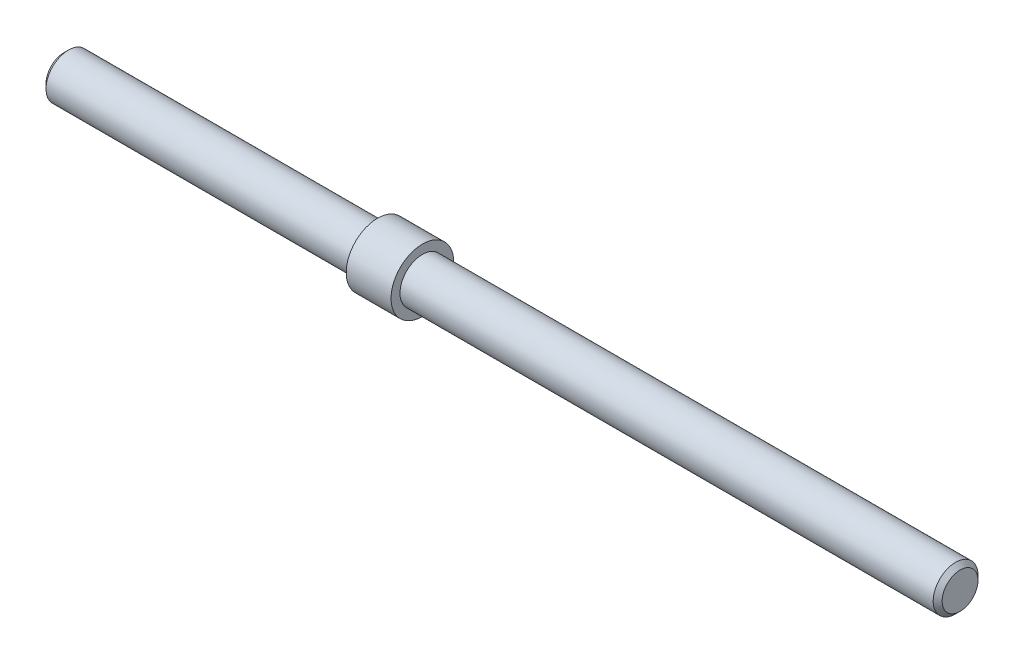
SolidWorks part; units mm, degrees
ref_plane "Ebene vorne" through (0, 0, 0) normal (0, 0, 1) x (1, 0, 0)
ref_plane "Ebene oben" through (0, 0, 0) normal (0, 1, 0) x (1, 0, 0)
ref_plane "Ebene rechts" through (0, 0, 0) normal (1, 0, 0) x (0, 0, -1)
sketch "Sketch1" plane through (0, 0, 0) normal (1, 0, 0) x (0, 0, -1)
  circle A0 centre (0, 0) radius 5
  dimension "D1" = 10
extrude "Boss-Extrude1" add sketch "Sketch1" along normal blind 200
chamfer "Chamfer1" distance 1 angle 45 2 edges at (200, 0, -5) (0, 0, -5)
sketch "Sketch2" plane through (0, 0, 0) normal (1, 0, 0) x (0, 0, -1)
  circle A0 centre (0, 0) radius 7
  dimension "D1" = 14
extrude "Boss-Extrude2" add sketch "Sketch2" along normal blind 10 from offset 70
